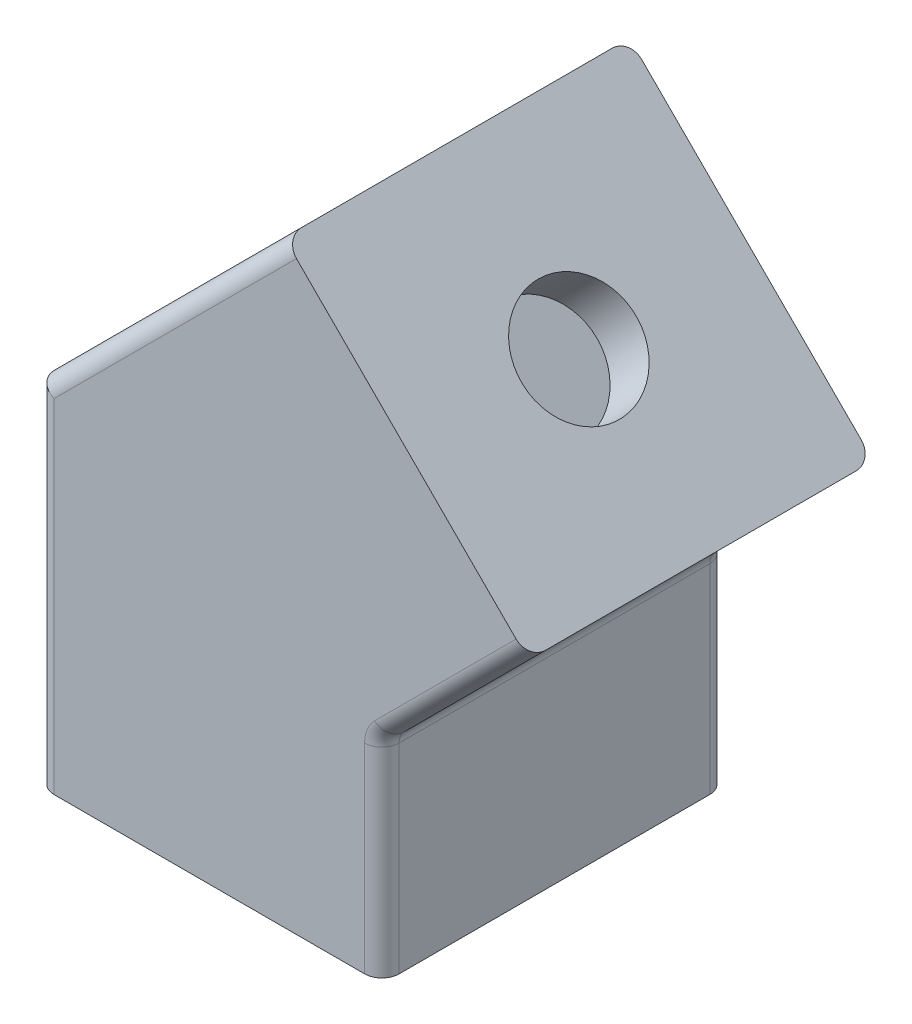
SolidWorks part; units mm, degrees
material "6063-T6"
ref_plane "Front Plane" through (0, 0, 0) normal (0, 0, 1) x (1, 0, 0)
ref_plane "Top Plane" through (0, 0, 0) normal (0, 1, 0) x (1, 0, 0)
ref_plane "Right Plane" through (0, 0, 0) normal (1, 0, 0) x (0, 0, -1)
sketch "Sketch1" plane through (0, 0, 0) normal (0, 0, 1) x (1, 0, 0)
  line L0 (0, -24) -> (0, 0)
  line L1 (0, 0) -> (16.9706, 16.9706)
  line L2 (16.9706, 16.9706) -> (-11.3137, 45.2548)
  line L3 (-11.3137, 45.2548) -> (-40, 16.5685)
  line L4 (-40, 16.5685) -> (-40, -24)
  line L5 (-40, -24) -> (0, -24)
  point P3 (0, -42.4703)
  dimension "D1" = 45
  dimension "D2" = 40
  dimension "D3" = 24
extrude "Boss-Extrude1" add sketch "Sketch1" along normal mid plane 40
shell "Shell1" thickness 3.3
sketch "Sketch2" plane through (0, -24, 0) normal (0, -1, 0) x (1, 0, 0)
  line L0 (-40, -20) -> (0, 20) construction
  circle A0 centre (-20, 0) radius 6.65
  point P6 (0, 0)
  dimension "D1" = 13.3
extrude "Cut-Extrude1" cut sketch "Sketch2" against normal up to next
sketch "Sketch3" plane through (16.9706, 16.9706, 0) normal (0.7071, 0.7071, 0) x (0, 0, -1)
  line L0 (-20, 0) -> (20, 40) construction
  circle A0 centre (0, 20) radius 6.65
  dimension "D1" = 13.3
extrude "Cut-Extrude2" cut sketch "Sketch3" against normal up to next
fillet "Fillet1" radius 2 10 edges at (8.4853, 8.4853, -20) (-3.3, 1.3669, 0) (-25.6569, 30.9117, 20) (-40, -3.7157, 20) (-25.6569, 30.9117, -20) (-40, -3.7157, -20) (0, -12, -20) (0, 0, 0) (0, -12, 20) (8.4853, 8.4853, 20)
